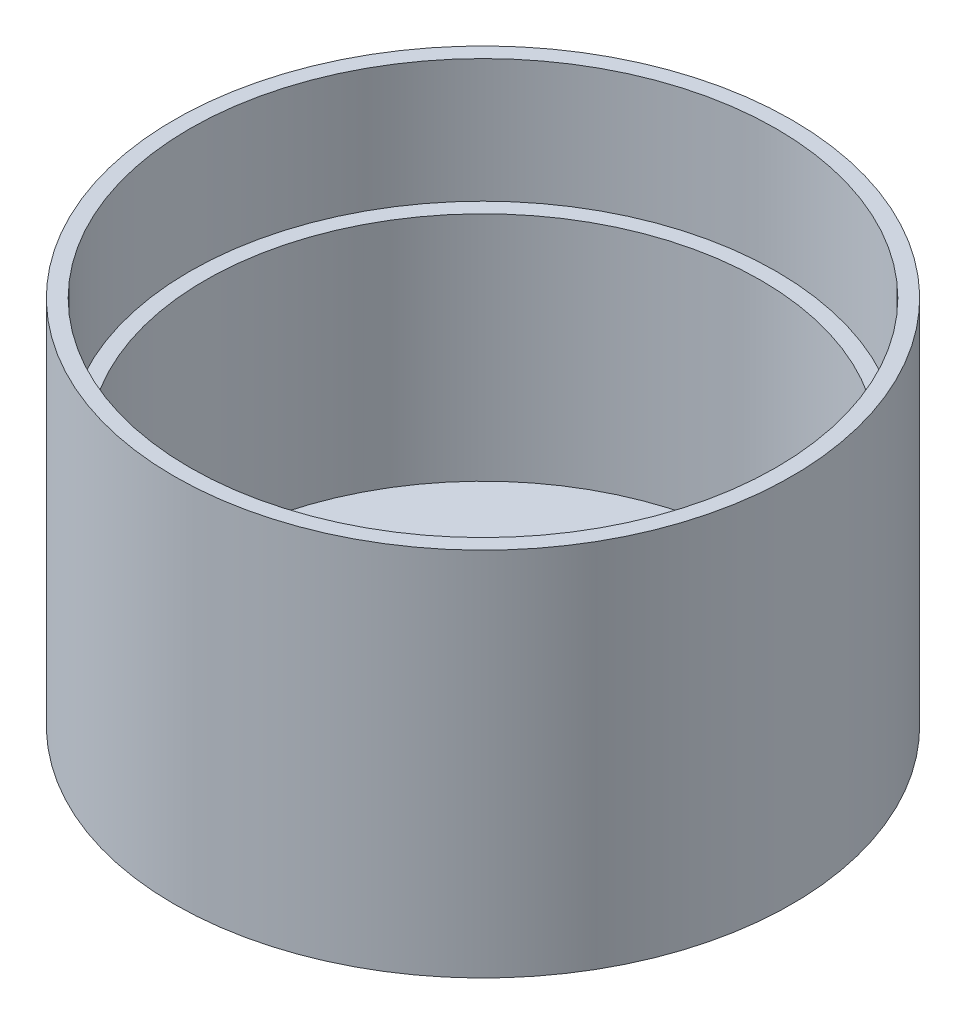
SolidWorks part; units mm, degrees
ref_plane "Front Plane" through (0, 0, 0) normal (0, 0, 1) x (1, 0, 0)
ref_plane "Top Plane" through (0, 0, 0) normal (0, 1, 0) x (1, 0, 0)
ref_plane "Right Plane" through (0, 0, 0) normal (1, 0, 0) x (0, 0, -1)
sketch "Sketch1" plane through (0, 0, 0) normal (0, 1, 0) x (1, 0, 0)
  circle A0 centre (0, 0) radius 63.5
  dimension "D1" = 127
extrude "Boss-Extrude1" add sketch "Sketch1" along normal blind 76.2
sketch "Sketch2" plane through (0, 76.2, 0) normal (0, 1, 0) x (1, 0, 0)
  circle A1 centre (0, 0) radius 57.15
  circle A2 centre (0, 0) radius 63.5 construction
  dimension "D1" = 6.35
extrude "Cut-Extrude1" cut sketch "Sketch2" against normal blind 73.025 contours A1
sketch "Sketch3" plane through (0, 76.2, 0) normal (0, 1, 0) x (1, 0, 0)
  circle A0 centre (0, 0) radius 60.325
  circle A1 centre (0, 0) radius 63.5 construction
  dimension "D1" = 3.175
extrude "Cut-Extrude2" cut sketch "Sketch3" against normal blind 25.4
